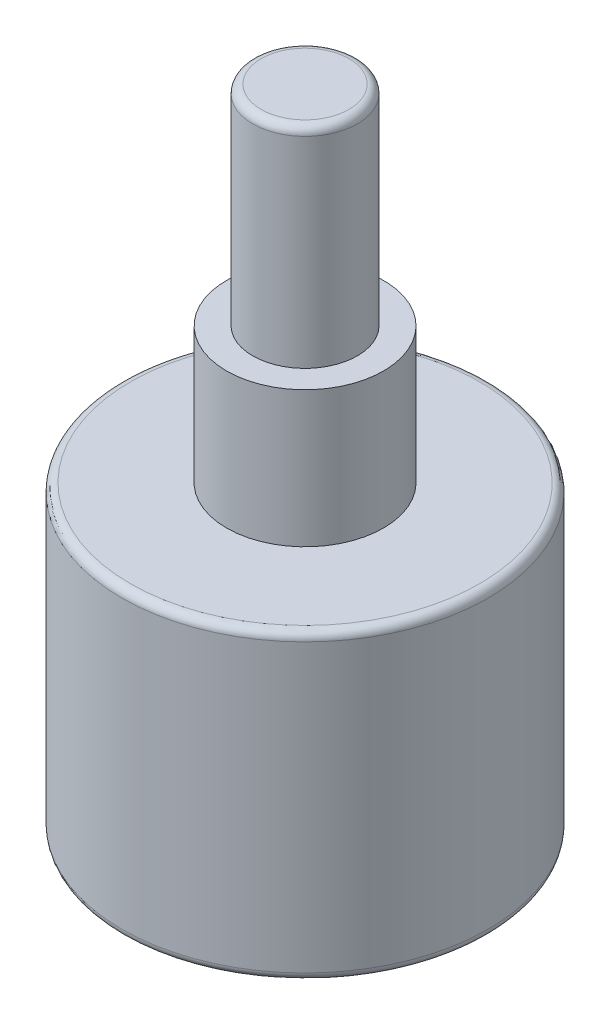
SolidWorks part; units mm, degrees
ref_plane "Front Plane" through (0, 0, 0) normal (0, 0, 1) x (1, 0, 0)
ref_plane "Top Plane" through (0, 0, 0) normal (0, 1, 0) x (1, 0, 0)
ref_plane "Right Plane" through (0, 0, 0) normal (1, 0, 0) x (0, 0, -1)
sketch "Sketch1" plane through (0, 0, 0) normal (0, 1, 0) x (1, 0, 0)
  circle A0 centre (0, 0) radius 11.1125
  dimension "D1" = 22.225
extrude "Boss-Extrude1" add sketch "Sketch1" along normal blind 18.415
sketch "Sketch2" plane through (0, 18.415, 0) normal (0, 1, 0) x (1, 0, 0)
  circle A0 centre (0, 0) radius 4.7625
extrude "Boss-Extrude2" add sketch "Sketch2" along normal blind 8.255
sketch "Sketch3" plane through (0, 26.67, 0) normal (0, 1, 0) x (1, 0, 0)
  circle A0 centre (0, 0) radius 3.175
extrude "Boss-Extrude3" add sketch "Sketch3" along normal blind 12.7
fillet "Fillet1" radius 0.508 2 edges at (0, 0, 11.1125) (0, 18.415, 11.1125)
fillet "Fillet2" radius 0.508 1 edges at (0, 39.37, 3.175)
